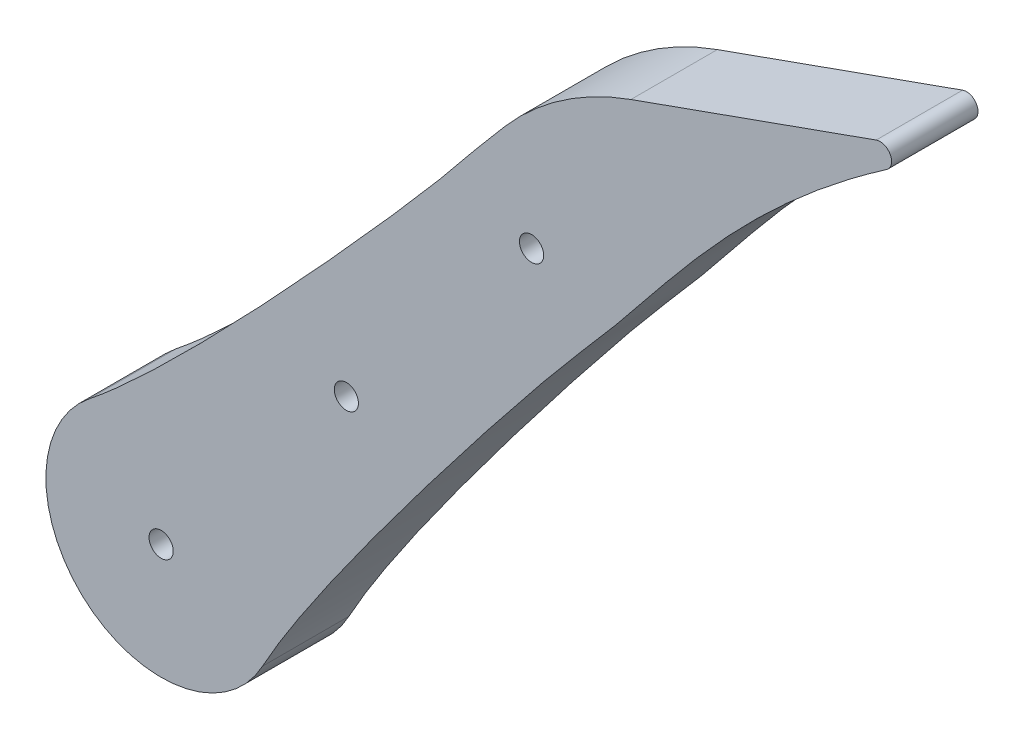
SolidWorks part; units mm, degrees
material "ABS"
ref_plane "Front Plane" through (0, 0, 0) normal (0, 0, 1) x (1, 0, 0)
ref_plane "Top Plane" through (0, 0, 0) normal (0, 1, 0) x (1, 0, 0)
ref_plane "Right Plane" through (0, 0, 0) normal (1, 0, 0) x (0, 0, -1)
sketch "Sketch3" plane through (0, 0, 16) normal (0, 0, 1) x (1, 0, 0)
  line L0 (141.7182, -118.9157) -> (13.1607, -272.1246) construction
  line L2 (135.2182, -125.4157) -> (148.2182, -125.4157) construction
  line L3 (135.2182, -125.4157) -> (135.2182, -112.4157) construction
  line L4 (135.2182, -112.4157) -> (148.2182, -112.4157) construction
  line L5 (148.2182, -125.4157) -> (148.2182, -112.4157) construction
  line L6 (135.2182, -125.4157) -> (148.2182, -112.4157) construction
  line L7 (135.2182, -112.4157) -> (148.2182, -125.4157) construction
  arc A0 (155.0191, -142.9851) -> (115.7048, -109.9965) centre (141.7182, -118.9157) ccw
  circle A1 centre (109.5788, -157.2179) radius 1.6 construction
  circle A2 centre (135.2182, -112.4157) radius 1.6
  arc A3 (0.7245, -256.4612) -> (30.7456, -281.652) centre (13.1607, -272.1246) ccw
  circle A4 centre (148.2182, -112.4157) radius 1.6
  circle A5 centre (148.2182, -125.4157) radius 1.6
  circle A6 centre (135.2182, -125.4157) radius 1.6
  circle A7 centre (77.4395, -195.5202) radius 1.6
  circle A8 centre (45.3001, -233.8224) radius 1.6
  circle A9 centre (13.1607, -272.1246) radius 1.6
  spline S0 degree 3 poles (115.7048, -109.9965) (101.9488, -150.1167) (78.1788, -171.7728) (58.7171, -197.0824) (16.357, -244.0495) (0.7245, -256.4612) knots 0 0 0 0 0.61909 0.71909 1 1 1 1
  spline S1 degree 3 poles (155.0191, -142.9851) (117.8971, -163.4989) (100.6976, -190.6684) (79.1521, -214.2294) (40.2542, -264.1017) (30.7456, -281.652) knots 0 0 0 0 0.61909 0.71909 1 1 1 1
extrude "Boss-Extrude1" add sketch "Sketch3" along normal blind 15
sketch "Sketch4" plane through (0, 0, 31) normal (0, 0, 1) x (1, 0, 0)
  line L0 (155.0191, -142.9851) -> (81.7852, -169.116)
  line L1 (81.7852, -169.116) -> (116.9009, -107.0687)
  arc A0 (146.6584, -145.9683) -> (116.9009, -107.0687) centre (141.7182, -118.9157) ccw
  spline S0 degree 3 poles (115.7048, -109.9965) (101.9488, -150.1167) (78.1788, -171.7728) (58.7171, -197.0824) (16.357, -244.0495) (0.7245, -256.4612) knots 0 0 0 0 0.61909 0.71909 1 1 1 1 construction
  dimension "D1" = 55
extrude "Cut-Extrude1" cut sketch "Sketch4" against normal blind 15
fillet "Fillet3" radius 2 1 edges at (155.0191, -142.9851, 23.5)
sketch "Sketch5" plane through (0, 0, 31) normal (0, 0, 1) x (1, 0, 0)
  circle A1 centre (77.4395, -195.5202) radius 2.1
  circle A2 centre (45.3001, -233.8224) radius 2.1
  circle A3 centre (13.1607, -272.1246) radius 2.1
  dimension "D1" = 4.2
  dimension "D2" = 4.2
  dimension "D3" = 4.2
extrude "Cut-Extrude2" cut sketch "Sketch5" against normal blind 15
fillet "Fillet4" radius 52 1 edges at (81.7852, -169.116, 23.5)
equation "\"thighLength\"=185"
equation "\"legLength\"=200"
equation "\"m3Thru\"=3.2"
equation "\"m4Thru\"=4.3"
equation "\"m3Insert\"=4.2"
equation "\"m4Insert\"=5.3"
equation "\"shoulder5mm\"=5.1"
equation "\"6706out\"=37.125"
equation "\"6706in\"=30"
equation "\"6904out\"=30.125"
equation "\"6904in\"=17"
equation "\"D1@Sketch5\"=\"m3Insert\" "
equation "\"D2@Sketch5\"=\"m3Insert\" "
equation "\"D3@Sketch5\"=\"m3Insert\" "
